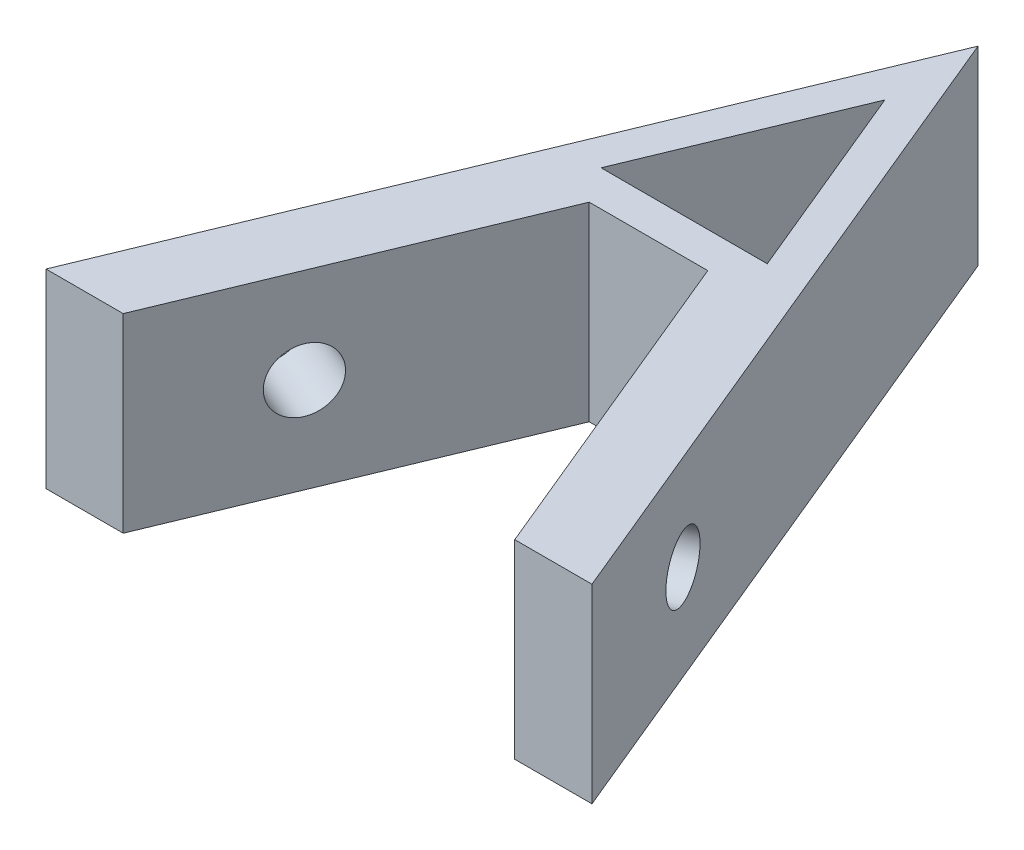
SolidWorks part; units mm, degrees
material "6061-T6 (SS)"
ref_plane "Front Plane" through (0, 0, 0) normal (0, 0, 1) x (1, 0, 0)
ref_plane "Top Plane" through (0, 0, 0) normal (0, 1, 0) x (1, 0, 0)
ref_plane "Right Plane" through (0, 0, 0) normal (1, 0, 0) x (0, 0, -1)
sketch "Sketch1" plane through (0, 0, 0) normal (0, 1, 0) x (1, 0, 0)
  line L0 (0, 0) -> (-22.961, -55.4328)
  line L1 (-22.961, -55.4328) -> (22.961, -55.4328)
  line L2 (22.961, -55.4328) -> (0, 0)
  point P4 (0, -55.4328)
  dimension "D1" = 45
  dimension "D2" = 60
extrude "Boss-Extrude1" add sketch "Sketch1" along normal blind 16
sketch "Sketch2" plane through (0, 16, 0) normal (0, 1, 0) x (1, 0, 0)
  line L6 (-16.4667, -55.4328) -> (-4.9861, -27.7164)
  line L7 (16.4667, -55.4328) -> (4.9861, -27.7164)
  line L8 (4.9861, -27.7164) -> (-4.9861, -27.7164)
  line L9 (-22.961, -55.4328) -> (22.961, -55.4328) construction
  line L10 (0, 0) -> (-22.961, -55.4328) construction
  line L11 (22.961, -55.4328) -> (0, 0) construction
  line L12 (-6.9907, -24.7164) -> (6.9907, -24.7164)
  line L13 (6.9907, -24.7164) -> (0, -7.8394)
  line L14 (0, -7.8394) -> (-6.9907, -24.7164)
  line L15 (-16.4667, -55.4328) -> (16.4667, -55.4328)
  dimension "D1" = 6
  dimension "D2" = 6
  dimension "D3" = 3
  dimension "30" = 30
  dimension "D4" = 3
extrude "Cut-Extrude1" cut sketch "Sketch2" against normal blind 16
sketch "Sketch3" plane through (0, 0, 0) normal (0.9239, 0, -0.3827) x (-0.3827, 0, -0.9239)
  line L0 (-60, 8) -> (0, 8) construction
  line L1 (-60, 16) -> (-60, 0) construction
  line L2 (0, 16) -> (0, 0) construction
  circle A0 centre (-45.85, 8) radius 2.65
  dimension "D1" = 5.3
  dimension "D2" = 14.15
sketch "Sketch4" plane through (0, 0, 0) normal (-0.9239, 0, -0.3827) x (-0.3827, 0, 0.9239)
  line L0 (0, 8) -> (60, 8) construction
  line L3 (60, 16) -> (60, 0) construction
  line L4 (0, 16) -> (0, 0) construction
  circle A0 centre (45.85, 8) radius 2.65
  dimension "D1" = 5.3
  dimension "D2" = 14.15
extrude "Cut-Extrude2" cut sketch "Sketch3" against normal blind 16
extrude "Cut-Extrude3" cut sketch "Sketch4" against normal blind 16
